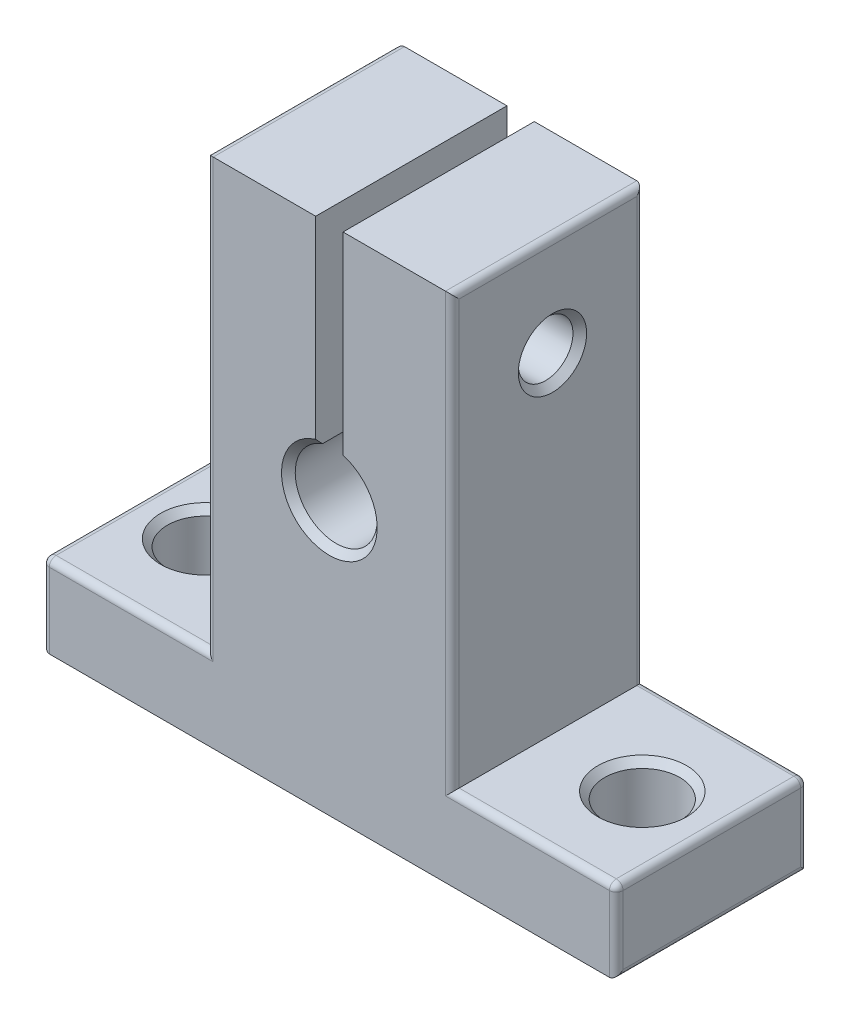
SolidWorks part; units mm, degrees
material "1060 Alloy"
ref_plane "Front Plane" through (0, 0, 0) normal (0, 0, 1) x (1, 0, 0)
ref_plane "Top Plane" through (0, 0, 0) normal (0, 1, 0) x (1, 0, 0)
ref_plane "Right Plane" through (0, 0, 0) normal (1, 0, 0) x (0, 0, -1)
sketch "Sketch1" plane through (0, 0, 0) normal (0, 0, 1) x (1, 0, 0)
  line L0 (0, 0) -> (-50000, 0) construction
  line L1 (0, 0) -> (0, 50000) construction
  line L2 (-21, -3) -> (-21, 3)
  line L3 (-21, 3) -> (-9, 3)
  line L4 (-9, 3) -> (-9, 34.5)
  line L5 (-9, 34.5) -> (-1, 34.5)
  line L6 (9, 34.5) -> (9, 3)
  line L7 (9, 3) -> (21, 3)
  line L8 (21, 3) -> (21, -3)
  line L9 (21, -3) -> (-21, -3)
  line L10 (16, -3) -> (16, 3) construction
  line L11 (-16, -3) -> (-16, 3) construction
  line L12 (-1, 34.5) -> (-1, 19.8284)
  line L13 (1, 34.5) -> (1, 19.8284)
  line L14 (1, 34.5) -> (9, 34.5)
  arc A0 (-1, 19.8284) -> (1, 19.8284) centre (0, 17) ccw
  point P8 (-21, 0)
  point P15 (0, -3)
  point P21 (16, 0)
  dimension "Shaft Diameter" = 6
  dimension "W" = 42
  dimension "P" = 18
  dimension "F" = 37.5
  dimension "G" = 6
  dimension "B" = 32
  dimension "D1" = 2
  dimension "h" = 20
extrude "Boss-Extrude1" add sketch "Sketch1" along normal mid plane 14
sketch "Sketch2" plane through (0, 3, 0) normal (0, 1, 0) x (1, 0, 0)
  line L0 (0, 0) -> (50000, 0) construction
  line L1 (0.3141, 0) -> (-49999.6859, 0) construction
  line L2 (-0.0955, 2.4842) -> (-0.0955, 50002.4842) construction
  circle A0 centre (15.9045, 0) radius 2.75
  circle A1 centre (-16.0955, 0) radius 2.75
  dimension "B" = 32
  dimension "S" = 5.5
extrude "Cut-Extrude1" cut sketch "Sketch2" against normal through all
sketch "Sketch5" plane through (-1, 0, 0) normal (1, 0, 0) x (0, 0, -1)
  line L0 (-7, 27.1642) -> (7, 27.1642) construction
  line L1 (7, 19.8284) -> (7, 34.5) construction
  line L2 (0, 34.5) -> (0, 19.8284) construction
  line L3 (-7, 34.5) -> (7, 34.5) construction
  line L4 (-7, 19.8284) -> (7, 19.8284) construction
  line L5 (-7, 19.8284) -> (-7, 34.5) construction
  circle A0 centre (0.3307, 27.1642) radius 2
  dimension "Clamping bold" = 4
extrude "Cut-Extrude2" cut sketch "Sketch5" against normal through all both and the other way through all
chamfer "Chamfer2" distance 0.5 angle 45 6 edges at (0, 14, -7) (0, 14, 7) (-9, 27.1642, -2.3307) (-13.3455, 3, 0) (9, 27.1642, 1.6693) (13.1545, 3, 0)
fillet "Fillet2" radius 0.5 18 edges at (21, -3, 0) (21, 0, 7) (21, 3, 0) (21, 0, -7) (-21, 3, 0) (-21, 0, 7) (-21, -3, 0) (-21, 0, -7) (-15, 3, -7) (-15, 3, 7) (-9, 18.75, 7) (-9, 34.5, 0) (-9, 18.75, -7) (9, 18.75, -7) (9, 18.75, 7) (15, 3, 7) (15, 3, -7) (9, 34.5, 0)
equation "\"W\"= \"W@Sketch1\"'Width"
equation "\"B\"= \"B@Sketch1\"'between hold"
equation "\"F\"= \"F@Sketch1\"'Hight"
equation "\"P\"= \"P@Sketch1\""
equation "\"G\"= \"G@Sketch1\""
equation "\"Shaft diameter\"= \"Shaft Diameter@Sketch1\""
equation "\"S\"= 5.5'M5"
equation "\"Clamping bold\"= 4'M4"
equation "\"h\"= \"h@Sketch1\""
